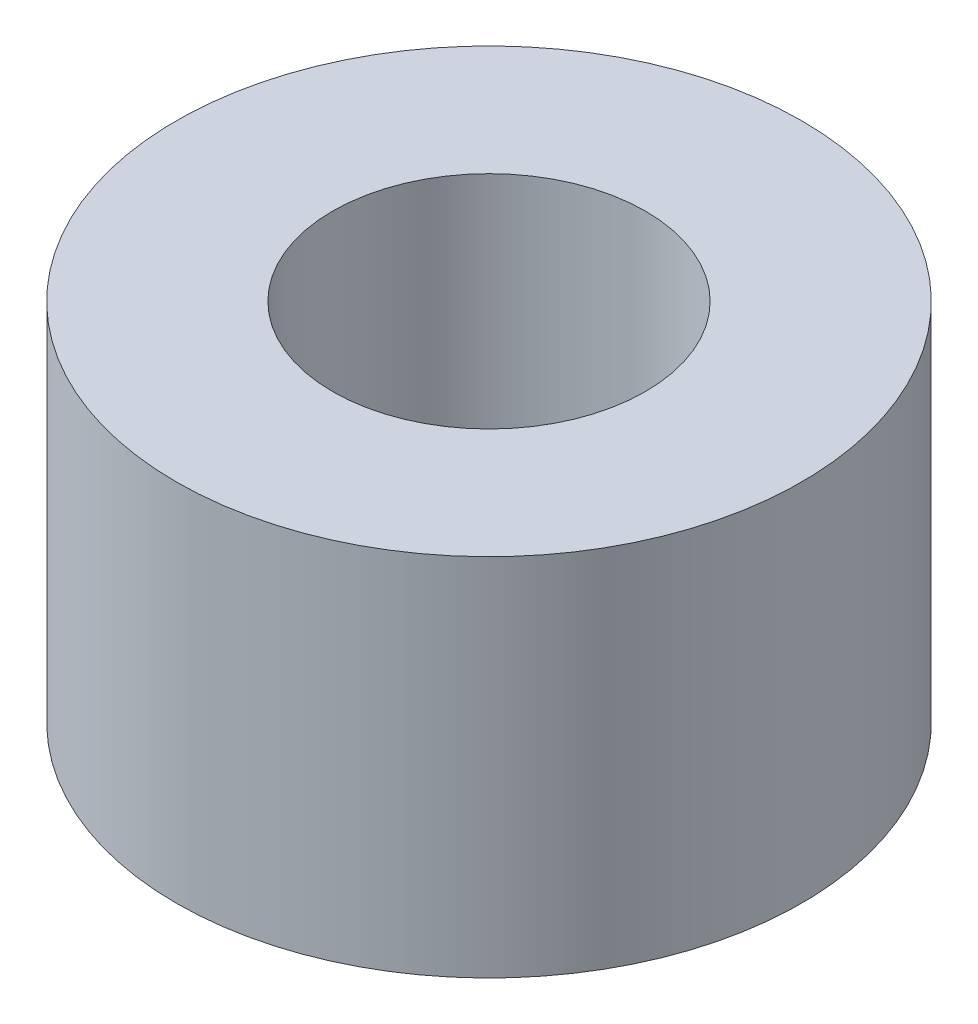
SolidWorks part; units mm, degrees
ref_plane "前视基准面" through (0, 0, 0) normal (0, 0, 1) x (1, 0, 0)
ref_plane "上视基准面" through (0, 0, 0) normal (0, 1, 0) x (1, 0, 0)
ref_plane "右视基准面" through (0, 0, 0) normal (1, 0, 0) x (0, 0, -1)
sketch "草图1" plane through (0, 0, 0) normal (0, 1, 0) x (1, 0, 0)
  circle A0 centre (0, 0) radius 3
  circle A1 centre (0, 0) radius 6
  dimension "D1" = 6
  dimension "D2" = 12
extrude "凸台-拉伸1" add sketch "草图1" along normal blind 7
